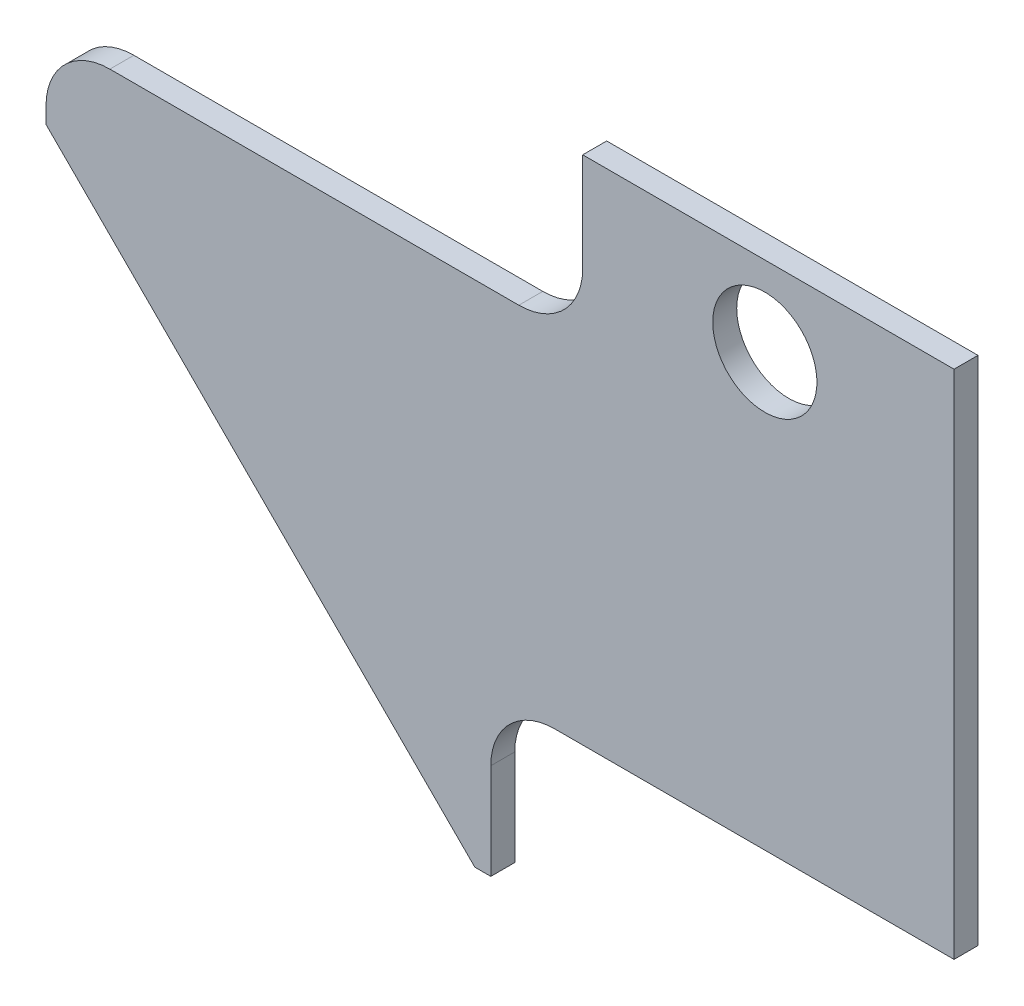
SolidWorks part; units mm, degrees
ref_plane "Front Plane" through (0, 0, 0) normal (0, 0, 1) x (1, 0, 0)
ref_plane "Top Plane" through (0, 0, 0) normal (0, 1, 0) x (1, 0, 0)
ref_plane "Right Plane" through (0, 0, 0) normal (1, 0, 0) x (0, 0, -1)
sketch "Sketch1" plane through (0, 0, 0) normal (0, 0, 1) x (1, 0, 0)
  line L0 (-138.2594, 48.9915) -> (32.2106, -121.4785)
  line L1 (32.2106, -121.4785) -> (222.7106, -121.4785)
  line L2 (-138.2594, 145.2215) -> (-138.2594, 48.9915)
  line L3 (-138.2594, 145.2215) -> (222.7106, 145.2215)
  line L4 (222.7106, -121.4785) -> (222.7106, 145.2215)
  circle A0 centre (147.4906, 113.4715) radius 20.701
  circle A2 centre (147.4906, 113.4715) radius 69.85 construction
  circle A3 centre (147.4906, 113.4715) radius 285.75 construction
  point P0 (0, 0)
  point P2 (147.4906, 113.4715)
  dimension "D4" = 234.95
  dimension "D1" = 45
  dimension "D2" = 266.7
  dimension "D5" = 247.65
extrude "Boss-Extrude1" add sketch "Sketch1" along normal blind 9.525
sketch "Sketch2" plane through (0, 0, 9.525) normal (0, 0, 1) x (1, 0, 0)
  line L0 (222.7106, 145.2215) -> (-138.2594, 145.2215) construction
  line L1 (222.7106, -121.4785) -> (38.5606, -121.4785)
  line L2 (222.7106, -121.4785) -> (222.7106, -57.9785)
  line L3 (222.7106, -57.9785) -> (38.5606, -57.9785)
  line L4 (38.5606, -121.4785) -> (38.5606, -57.9785)
  line L5 (75.1006, 145.2215) -> (-138.2594, 145.2215)
  line L6 (75.1006, 145.2215) -> (75.1006, 80.7415)
  line L7 (75.1006, 80.7415) -> (-138.2594, 80.7415)
  line L8 (-138.2594, 145.2215) -> (-138.2594, 80.7415)
  line L9 (-138.2594, 145.2215) -> (-138.2594, 48.9915) construction
  dimension "D1" = 31.75
  dimension "D2" = 6.35
extrude "Cut-Extrude1" cut sketch "Sketch2" against normal through all
fillet "Fillet1" radius 25.4 1 edges at (75.1006, 80.7415, 4.7625)
fillet "Fillet2" radius 25.4 2 edges at (38.5606, -57.9785, 4.7625) (-138.2594, 80.7415, 4.7625)
